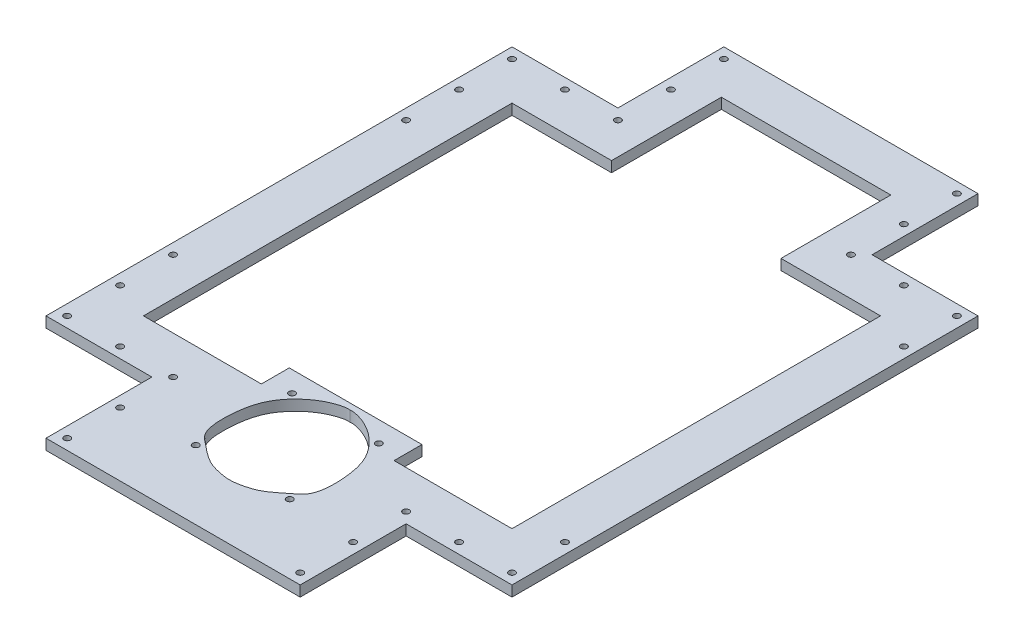
SolidWorks part; units mm, degrees
ref_plane "Plan de face" through (0, 0, 0) normal (0, 0, 1) x (1, 0, 0)
ref_plane "Plan de dessus" through (0, 0, 0) normal (0, 1, 0) x (1, 0, 0)
ref_plane "Plan de droite" through (0, 0, 0) normal (1, 0, 0) x (0, 0, -1)
sketch "Esquisse1" plane through (0, 0, 0) normal (0, 1, 0) x (1, 0, 0)
  line L0 (-60, 110) -> (-60, 160)
  line L1 (110, -110) -> (60, -110)
  line L2 (110, -110) -> (110, 110)
  line L3 (110, 110) -> (60, 110)
  line L4 (-110, -110) -> (-110, 0)
  line L5 (110, -110) -> (-110, 110) construction
  line L6 (110, 110) -> (-110, -110) construction
  line L7 (-60, 160) -> (60, 160)
  line L8 (60, 160) -> (60, 110)
  line L9 (0, 160) -> (0, -160) construction
  line L10 (-110, 0) -> (110, 0) construction
  line L11 (-105, -105) -> (-105, -50) construction
  line L12 (-55, -105) -> (-55, -160) construction
  line L13 (-60, 110) -> (-110, 110)
  line L14 (60, -160) -> (60, -110)
  line L15 (-60, -160) -> (60, -160)
  line L16 (-60, -110) -> (-60, -160)
  line L17 (-60, -110) -> (-110, -110)
  line L23 (-40, 138.8364) -> (40, 138.8364)
  line L28 (-110, 0) -> (-110, 110)
  line L33 (-105, -105) -> (105, -105) construction
  line L34 (105, -105) -> (105, 0) construction
  line L35 (87, -87) -> (31.3269, -87)
  line L36 (87, -87) -> (87, 87)
  line L37 (87, 87) -> (40, 87)
  line L38 (-87, -87) -> (-87, 87)
  line L39 (87, -87) -> (-87, 87) construction
  line L40 (87, 87) -> (-87, -87) construction
  line L41 (40, 138.8364) -> (40, 87)
  line L42 (-40, 138.8364) -> (-40, 87)
  line L46 (-40, 87) -> (-87, 87)
  line L48 (-20.2639, -83.5808) -> (20.6869, -83.5808) construction
  line L49 (0.2938, -104.662) -> (0.2938, -133.662) construction
  line L50 (20.6869, -83.5808) -> (22.477, -127.41) construction
  line L51 (22.477, -127.41) -> (-21.8046, -127.506) construction
  line L52 (-21.8046, -127.506) -> (-20.2639, -83.5808) construction
  line L53 (-20.2639, -83.5808) -> (22.477, -127.41) construction
  line L54 (-21.8046, -127.506) -> (20.6869, -83.5808) construction
  line L55 (-31.3269, -87) -> (-87, -87)
  line L57 (31.3269, -87) -> (31.3269, -73.8394)
  line L58 (31.3269, -73.8394) -> (-31.3269, -73.8394)
  line L59 (-31.3269, -87) -> (-31.3269, -73.8394)
  line L60 (0, -87) -> (-31.3269, -73.8394) construction
  line L61 (31.3269, -73.8394) -> (0, -87) construction
  circle A0 centre (-105, -105) radius 1.5
  circle A1 centre (-105, -55) radius 1.5
  circle A2 centre (-55, -105) radius 1.5
  circle A5 centre (-5, -105) radius 1.5 [skipped]
  circle A6 centre (45, -105) radius 1.5 [skipped]
  circle A7 centre (-55, -155) radius 1.5
  circle A8 centre (-55, 155) radius 1.5
  circle A9 centre (-55, 105) radius 1.5
  circle A10 centre (-105, 105) radius 1.5
  circle A11 centre (-105, 55) radius 1.5
  circle A12 centre (55, -155) radius 1.5
  circle A13 centre (55, -105) radius 1.5
  circle A14 centre (105, -105) radius 1.5
  circle A15 centre (105, 105) radius 1.5
  circle A16 centre (55, 105) radius 1.5
  circle A17 centre (55, 155) radius 1.5
  circle A18 centre (-20.2639, -83.5808) radius 1.5
  circle A19 centre (20.6869, -83.5808) radius 1.5
  circle A20 centre (22.477, -127.41) radius 1.5
  circle A21 centre (-21.8046, -127.506) radius 1.5
  spline S0 degree 3 poles (0.2938, -76.7263) (-0.9961, -76.5783) (-4.6992, -77.2074) (-11.369, -80.0208) (-17.3381, -84.8957) (-23.6991, -93.0991) (-26.4738, -103.394) (-26.3988, -120.1644) (-18.9208, -125.4305) (-12.7349, -130.8054) (-5.3206, -133.1674) (-1.1322, -133.8105) (0.2938, -133.662) knots 0 0 0 0 0.044372 0.129133 0.24756 0.307902 0.482602 0.644889 0.731533 0.853727 0.90962 1 1 1 1
  spline S1 degree 3 poles (0.2938, -76.7263) (1.5836, -76.5783) (5.2868, -77.2074) (11.9565, -80.0208) (17.9257, -84.8957) (24.2867, -93.0991) (27.0614, -103.394) (26.9864, -120.1644) (19.5084, -125.4305) (13.3225, -130.8054) (5.9082, -133.1674) (1.7198, -133.8105) (0.2938, -133.662) knots 0 0 0 0 0.044372 0.129133 0.24756 0.307902 0.482602 0.644889 0.731533 0.853727 0.90962 1 1 1 1
  point P0 (0, 0)
  point P23 (0, 0)
  point P24 (0, 0)
  point P32 (0, 138.8364)
  point P33 (0, 0)
  point P36 (0, -105)
  point P68 (-21.8046, -127.506)
  point P70 (22.477, -127.41)
  point P71 (20.6869, -83.5808)
  point P72 (-20.2639, -83.5808)
  point P77 (0.2938, -104.662)
  dimension "D4" = 3
  dimension "D6" = 50
  dimension "D14" = 5
  dimension "D16" = 5
  dimension "D10" = 21.1636
  dimension "D11" = 29
  dimension "D12" = 40.9508
  dimension "D8" = 23
  dimension "D1" = 220
  dimension "D2" = 50
  dimension "D3" = 50
  dimension "D5" = 5
  dimension "D7" = 120
  dimension "D9" = 20
  dimension "D13" = 2
  dimension "D18" = 44.2816
  dimension "D19" = 92.009
  dimension "D20" = 92.339
  dimension "D21" = 87.867
  dimension "D15" = 4
  dimension "D17" = 2
extrude "Boss.-Extru.1" add sketch "Esquisse1" along normal blind 5
sketch "Esquisse2" plane through (0, 5, 0) normal (0, 1, 0) x (1, 0, 0)
  line L0 (-105, -55) -> (-105, -105) construction
  line L1 (-105, -105) -> (-55, -105) construction
  line L2 (-55, -105) -> (-55, -155) construction
  line L3 (0, -160) -> (0, 160) construction
  line L4 (-60, -160) -> (60, -160) construction
  line L5 (60, 160) -> (-60, 160) construction
  line L6 (-110, 0) -> (110, 0) construction
  line L7 (-110, 110) -> (-110, -110) construction
  line L8 (110, -110) -> (110, 110) construction
  circle A0 centre (-105, -80) radius 1.5
  circle A1 centre (-80, -105) radius 1.5
  circle A2 centre (-55, -130) radius 1.5
  circle A3 centre (55, -130) radius 1.5
  circle A4 centre (80, -105) radius 1.5
  circle A5 centre (105, -80) radius 1.5
  circle A6 centre (105, 80) radius 1.5
  circle A7 centre (80, 105) radius 1.5
  circle A8 centre (55, 130) radius 1.5
  circle A9 centre (-55, 130) radius 1.5
  circle A10 centre (-80, 105) radius 1.5
  circle A11 centre (-105, 80) radius 1.5
  dimension "D1" = 3
extrude "Enlèv. mat.-Extru.1" cut sketch "Esquisse2" against normal up to surface (5 mm away) up to face at (-21.8046, 0, 129.006)
